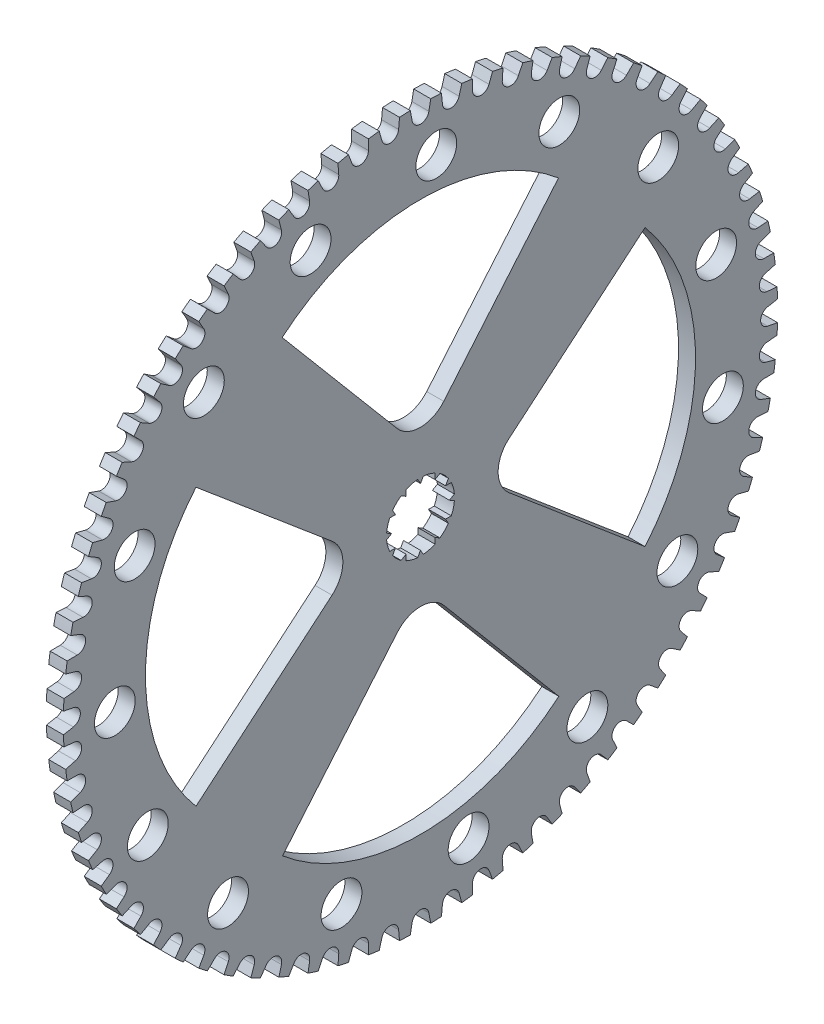
SolidWorks part; units mm, degrees
material "Chrome Stainless Steel"
ref_plane "Front Plane" through (0, 0, 0) normal (0, 0, 1) x (1, 0, 0)
ref_plane "Top Plane" through (0, 0, 0) normal (0, 1, 0) x (1, 0, 0)
ref_plane "Right Plane" through (0, 0, 0) normal (1, 0, 0) x (0, 0, -1)
sketch "Sketch1" plane through (0, 0, 0) normal (1, 0, 0) x (0, 0, -1)
  circle A0 centre (0, 0) radius 105
  dimension "D1" = 210
extrude "Boss-Extrude1" add sketch "Sketch1" along normal blind 5
sketch "Sketch3" plane through (0, 0, 0) normal (-1, 0, 0) x (0, 0, 1)
  line L0 (-2.4578, 102.0428) -> (-3, 104.9571)
  line L1 (2.4578, 102.0428) -> (3, 104.9571)
  line L2 (6.4451, 101.8687) -> (6.159, 104.8192)
  line L3 (11.3421, 101.4402) -> (12.1362, 104.2963)
  line L4 (15.299, 100.9193) -> (15.2712, 103.8835)
  line L5 (20.14, 100.0657) -> (21.18, 102.8417)
  line L6 (24.0365, 99.2019) -> (24.2671, 102.1573)
  line L7 (28.7847, 97.9296) -> (30.0627, 100.6043)
  line L8 (32.5911, 96.7295) -> (33.0784, 99.6535)
  line L9 (37.2103, 95.0482) -> (38.7165, 97.6014)
  line L10 (40.8976, 93.5209) -> (41.6379, 96.3913)
  line L11 (45.3527, 91.4434) -> (47.0757, 93.8556)
  line L12 (48.8928, 89.6005) -> (49.8805, 92.3955)
  line L13 (53.1499, 87.1427) -> (55.0766, 89.3955)
  line L14 (56.516, 84.9983) -> (57.7435, 87.6966)
  line L15 (60.5427, 82.1788) -> (62.6584, 84.2551)
  line L16 (63.709, 79.7492) -> (65.167, 82.3302)
  line L17 (67.4746, 76.5894) -> (69.7633, 78.4735)
  line L18 (70.4172, 73.8931) -> (72.0946, 76.3372)
  line L19 (73.8931, 70.4172) -> (76.3372, 72.0946)
  line L20 (76.5894, 67.4746) -> (78.4735, 69.7633)
  line L21 (79.7492, 63.709) -> (82.3302, 65.167)
  line L22 (82.1788, 60.5427) -> (84.2551, 62.6584)
  line L23 (84.9983, 56.516) -> (87.6966, 57.7435)
  line L24 (87.1427, 53.1499) -> (89.3955, 55.0766)
  line L25 (89.6005, 48.8928) -> (92.3955, 49.8805)
  line L26 (91.4434, 45.3527) -> (93.8556, 47.0757)
  line L27 (93.5209, 40.8976) -> (96.3913, 41.6379)
  line L28 (95.0482, 37.2103) -> (97.6014, 38.7165)
  line L29 (96.7295, 32.5911) -> (99.6535, 33.0784)
  line L30 (97.9296, 28.7847) -> (100.6043, 30.0627)
  line L31 (99.2019, 24.0365) -> (102.1573, 24.2671)
  line L32 (100.0657, 20.14) -> (102.8417, 21.18)
  line L33 (100.9193, 15.299) -> (103.8835, 15.2712)
  line L34 (101.4402, 11.3421) -> (104.2963, 12.1362)
  line L35 (101.8687, 6.4451) -> (104.8192, 6.159)
  line L36 (102.0428, 2.4578) -> (104.9571, 3)
  line L37 (102.0428, -2.4578) -> (104.9571, -3)
  line L38 (101.8687, -6.4451) -> (104.8192, -6.159)
  line L39 (101.4402, -11.3421) -> (104.2963, -12.1362)
  line L40 (100.9193, -15.299) -> (103.8835, -15.2712)
  line L41 (100.0657, -20.14) -> (102.8417, -21.18)
  line L42 (99.2019, -24.0365) -> (102.1573, -24.2671)
  line L43 (97.9296, -28.7847) -> (100.6043, -30.0627)
  line L44 (96.7295, -32.5911) -> (99.6535, -33.0784)
  line L45 (95.0482, -37.2103) -> (97.6014, -38.7165)
  line L46 (93.5209, -40.8976) -> (96.3913, -41.6379)
  line L47 (91.4434, -45.3527) -> (93.8556, -47.0757)
  line L48 (89.6005, -48.8928) -> (92.3955, -49.8805)
  line L49 (87.1427, -53.1499) -> (89.3955, -55.0766)
  line L50 (84.9983, -56.516) -> (87.6966, -57.7435)
  line L51 (82.1788, -60.5427) -> (84.2551, -62.6584)
  line L52 (79.7492, -63.709) -> (82.3302, -65.167)
  line L53 (76.5894, -67.4746) -> (78.4735, -69.7633)
  line L54 (73.8931, -70.4172) -> (76.3372, -72.0946)
  line L55 (70.4172, -73.8931) -> (72.0946, -76.3372)
  line L56 (67.4746, -76.5894) -> (69.7633, -78.4735)
  line L57 (63.709, -79.7492) -> (65.167, -82.3302)
  line L58 (60.5427, -82.1788) -> (62.6584, -84.2551)
  line L59 (56.516, -84.9983) -> (57.7435, -87.6966)
  line L60 (53.1499, -87.1427) -> (55.0766, -89.3955)
  line L61 (48.8928, -89.6005) -> (49.8805, -92.3955)
  line L62 (45.3527, -91.4434) -> (47.0757, -93.8556)
  line L63 (40.8976, -93.5209) -> (41.6379, -96.3913)
  line L64 (37.2103, -95.0482) -> (38.7165, -97.6014)
  line L65 (32.5911, -96.7295) -> (33.0784, -99.6535)
  line L66 (28.7847, -97.9296) -> (30.0627, -100.6043)
  line L67 (24.0365, -99.2019) -> (24.2671, -102.1573)
  line L68 (20.14, -100.0657) -> (21.18, -102.8417)
  line L69 (15.299, -100.9193) -> (15.2712, -103.8835)
  line L70 (11.3421, -101.4402) -> (12.1362, -104.2963)
  line L71 (6.4451, -101.8687) -> (6.159, -104.8192)
  line L72 (2.4578, -102.0428) -> (3, -104.9571)
  line L73 (-2.4578, -102.0428) -> (-3, -104.9571)
  line L74 (-6.4451, -101.8687) -> (-6.159, -104.8192)
  line L75 (-11.3421, -101.4402) -> (-12.1362, -104.2963)
  line L76 (-15.299, -100.9193) -> (-15.2712, -103.8835)
  line L77 (-20.14, -100.0657) -> (-21.18, -102.8417)
  line L78 (-24.0365, -99.2019) -> (-24.2671, -102.1573)
  line L79 (-28.7847, -97.9296) -> (-30.0627, -100.6043)
  line L80 (-32.5911, -96.7295) -> (-33.0784, -99.6535)
  line L81 (-37.2103, -95.0482) -> (-38.7165, -97.6014)
  line L82 (-40.8976, -93.5209) -> (-41.6379, -96.3913)
  line L83 (-45.3527, -91.4434) -> (-47.0757, -93.8556)
  line L84 (-48.8928, -89.6005) -> (-49.8805, -92.3955)
  line L85 (-53.1499, -87.1427) -> (-55.0766, -89.3955)
  line L86 (-56.516, -84.9983) -> (-57.7435, -87.6966)
  line L87 (-60.5427, -82.1788) -> (-62.6584, -84.2551)
  line L88 (-63.709, -79.7492) -> (-65.167, -82.3302)
  line L89 (-67.4746, -76.5894) -> (-69.7633, -78.4735)
  line L90 (-70.4172, -73.8931) -> (-72.0946, -76.3372)
  line L91 (-73.8931, -70.4172) -> (-76.3372, -72.0946)
  line L92 (-76.5894, -67.4746) -> (-78.4735, -69.7633)
  line L93 (-79.7492, -63.709) -> (-82.3302, -65.167)
  line L94 (-82.1788, -60.5427) -> (-84.2551, -62.6584)
  line L95 (-84.9983, -56.516) -> (-87.6966, -57.7435)
  line L96 (-87.1427, -53.1499) -> (-89.3955, -55.0766)
  line L97 (-89.6005, -48.8928) -> (-92.3955, -49.8805)
  line L98 (-91.4434, -45.3527) -> (-93.8556, -47.0757)
  line L99 (-93.5209, -40.8976) -> (-96.3913, -41.6379)
  line L100 (-95.0482, -37.2103) -> (-97.6014, -38.7165)
  line L101 (-96.7295, -32.5911) -> (-99.6535, -33.0784)
  line L102 (-97.9296, -28.7847) -> (-100.6043, -30.0627)
  line L103 (-99.2019, -24.0365) -> (-102.1573, -24.2671)
  line L104 (-100.0657, -20.14) -> (-102.8417, -21.18)
  line L105 (-100.9193, -15.299) -> (-103.8835, -15.2712)
  line L106 (-101.4402, -11.3421) -> (-104.2963, -12.1362)
  line L107 (-101.8687, -6.4451) -> (-104.8192, -6.159)
  line L108 (-102.0428, -2.4578) -> (-104.9571, -3)
  line L109 (-102.0428, 2.4578) -> (-104.9571, 3)
  line L110 (-101.8687, 6.4451) -> (-104.8192, 6.159)
  line L111 (-101.4402, 11.3421) -> (-104.2963, 12.1362)
  line L112 (-100.9193, 15.299) -> (-103.8835, 15.2712)
  line L113 (-100.0657, 20.14) -> (-102.8417, 21.18)
  line L114 (-99.2019, 24.0365) -> (-102.1573, 24.2671)
  line L115 (-97.9296, 28.7847) -> (-100.6043, 30.0627)
  line L116 (-96.7295, 32.5911) -> (-99.6535, 33.0784)
  line L117 (-95.0482, 37.2103) -> (-97.6014, 38.7165)
  line L118 (-93.5209, 40.8976) -> (-96.3913, 41.6379)
  line L119 (-91.4434, 45.3527) -> (-93.8556, 47.0757)
  line L120 (-89.6005, 48.8928) -> (-92.3955, 49.8805)
  line L121 (-87.1427, 53.1499) -> (-89.3955, 55.0766)
  line L122 (-84.9983, 56.516) -> (-87.6966, 57.7435)
  line L123 (-82.1788, 60.5427) -> (-84.2551, 62.6584)
  line L124 (-79.7492, 63.709) -> (-82.3302, 65.167)
  line L125 (-76.5894, 67.4746) -> (-78.4735, 69.7633)
  line L126 (-73.8931, 70.4172) -> (-76.3372, 72.0946)
  line L127 (-70.4172, 73.8931) -> (-72.0946, 76.3372)
  line L128 (-67.4746, 76.5894) -> (-69.7633, 78.4735)
  line L129 (-63.709, 79.7492) -> (-65.167, 82.3302)
  line L130 (-60.5427, 82.1788) -> (-62.6584, 84.2551)
  line L131 (-56.516, 84.9983) -> (-57.7435, 87.6966)
  line L132 (-53.1499, 87.1427) -> (-55.0766, 89.3955)
  line L133 (-48.8928, 89.6005) -> (-49.8805, 92.3955)
  line L134 (-45.3527, 91.4434) -> (-47.0757, 93.8556)
  line L135 (-40.8976, 93.5209) -> (-41.6379, 96.3913)
  line L136 (-37.2103, 95.0482) -> (-38.7165, 97.6014)
  line L137 (-32.5911, 96.7295) -> (-33.0784, 99.6535)
  line L138 (-28.7847, 97.9296) -> (-30.0627, 100.6043)
  line L139 (-24.0365, 99.2019) -> (-24.2671, 102.1573)
  line L140 (-20.14, 100.0657) -> (-21.18, 102.8417)
  line L141 (-15.299, 100.9193) -> (-15.2712, 103.8835)
  line L142 (-11.3421, 101.4402) -> (-12.1362, 104.2963)
  line L143 (-6.4451, 101.8687) -> (-6.159, 104.8192)
  line L164 (-0.8454, 9.9642) -> (0, 8.5)
  line L167 (0, 8.5) -> (0.8454, 9.9642)
  line L170 (4.25, 9.0519) -> (4.25, 7.3612)
  line L171 (4.25, 7.3612) -> (5.7142, 8.2066)
  line L172 (8.2066, 5.7142) -> (7.3612, 4.25)
  line L173 (7.3612, 4.25) -> (9.0519, 4.25)
  line L174 (9.9642, 0.8454) -> (8.5, 0)
  line L175 (8.5, 0) -> (9.9642, -0.8454)
  line L176 (9.0519, -4.25) -> (7.3612, -4.25)
  line L177 (7.3612, -4.25) -> (8.2066, -5.7142)
  line L178 (5.7142, -8.2066) -> (4.25, -7.3612)
  line L179 (4.25, -7.3612) -> (4.25, -9.0519)
  line L180 (0.8454, -9.9642) -> (0, -8.5)
  line L181 (0, -8.5) -> (-0.8454, -9.9642)
  line L182 (-4.25, -9.0519) -> (-4.25, -7.3612)
  line L183 (-4.25, -7.3612) -> (-5.7142, -8.2066)
  line L184 (-8.2066, -5.7142) -> (-7.3612, -4.25)
  line L185 (-7.3612, -4.25) -> (-9.0519, -4.25)
  line L186 (-9.9642, -0.8454) -> (-8.5, 0)
  line L187 (-8.5, 0) -> (-9.9642, 0.8454)
  line L188 (-9.0519, 4.25) -> (-7.3612, 4.25)
  line L189 (-7.3612, 4.25) -> (-8.2066, 5.7142)
  line L190 (-5.7142, 8.2066) -> (-4.25, 7.3612)
  line L191 (-4.25, 7.3612) -> (-4.25, 9.0519)
  arc A0 (2.4578, 102.0428) -> (-2.4578, 102.0428) centre (0, 102.5) cw
  circle A1 centre (0, 0) radius 105 construction
  circle A2 centre (0, 0) radius 100 construction
  arc A3 (-3, 104.9571) -> (3, 104.9571) centre (0, 0) cw
  arc A4 (11.3421, 101.4402) -> (6.4451, 101.8687) centre (8.9335, 102.11) cw
  arc A5 (6.159, 104.8192) -> (12.1362, 104.2963) centre (0, 0) cw
  arc A6 (20.14, 100.0657) -> (15.299, 100.9193) centre (17.7989, 100.9428) cw
  arc A7 (15.2712, 103.8835) -> (21.18, 102.8417) centre (0, 0) cw
  arc A8 (28.7847, 97.9296) -> (24.0365, 99.2019) centre (26.529, 99.0074) cw
  arc A9 (24.2671, 102.1573) -> (30.0627, 100.6043) centre (0, 0) cw
  arc A10 (37.2103, 95.0482) -> (32.5911, 96.7295) centre (35.0571, 96.3185) cw
  arc A11 (33.0784, 99.6535) -> (38.7165, 97.6014) centre (0, 0) cw
  arc A12 (45.3527, 91.4434) -> (40.8976, 93.5209) centre (43.3184, 92.8965) cw
  arc A13 (41.6379, 96.3913) -> (47.0757, 93.8556) centre (0, 0) cw
  arc A14 (53.1499, 87.1427) -> (48.8928, 89.6005) centre (51.25, 88.7676) cw
  arc A15 (49.8805, 92.3955) -> (55.0766, 89.3955) centre (0, 0) cw
  arc A16 (60.5427, 82.1788) -> (56.516, 84.9983) centre (58.7916, 83.9631) cw
  arc A17 (57.7435, 87.6966) -> (62.6584, 84.2551) centre (0, 0) cw
  arc A18 (67.4746, 76.5894) -> (63.709, 79.7492) centre (65.8857, 78.5196) cw
  arc A19 (65.167, 82.3302) -> (69.7633, 78.4735) centre (0, 0) cw
  arc A20 (73.8931, 70.4172) -> (70.4172, 73.8931) centre (72.4784, 72.4784) cw
  arc A21 (72.0946, 76.3372) -> (76.3372, 72.0946) centre (0, 0) cw
  arc A22 (79.7492, 63.709) -> (76.5894, 67.4746) centre (78.5196, 65.8857) cw
  arc A23 (78.4735, 69.7633) -> (82.3302, 65.167) centre (0, 0) cw
  arc A24 (84.9983, 56.516) -> (82.1788, 60.5427) centre (83.9631, 58.7916) cw
  arc A25 (84.2551, 62.6584) -> (87.6966, 57.7435) centre (0, 0) cw
  arc A26 (89.6005, 48.8928) -> (87.1427, 53.1499) centre (88.7676, 51.25) cw
  arc A27 (89.3955, 55.0766) -> (92.3955, 49.8805) centre (0, 0) cw
  arc A28 (93.5209, 40.8976) -> (91.4434, 45.3527) centre (92.8965, 43.3184) cw
  arc A29 (93.8556, 47.0757) -> (96.3913, 41.6379) centre (0, 0) cw
  arc A30 (96.7295, 32.5911) -> (95.0482, 37.2103) centre (96.3185, 35.0571) cw
  arc A31 (97.6014, 38.7165) -> (99.6535, 33.0784) centre (0, 0) cw
  arc A32 (99.2019, 24.0365) -> (97.9296, 28.7847) centre (99.0074, 26.529) cw
  arc A33 (100.6043, 30.0627) -> (102.1573, 24.2671) centre (0, 0) cw
  arc A34 (100.9193, 15.299) -> (100.0657, 20.14) centre (100.9428, 17.7989) cw
  arc A35 (102.8417, 21.18) -> (103.8835, 15.2712) centre (0, 0) cw
  arc A36 (101.8687, 6.4451) -> (101.4402, 11.3421) centre (102.11, 8.9335) cw
  arc A37 (104.2963, 12.1362) -> (104.8192, 6.159) centre (0, 0) cw
  arc A38 (102.0428, -2.4578) -> (102.0428, 2.4578) centre (102.5, 0) cw
  arc A39 (104.9571, 3) -> (104.9571, -3) centre (0, 0) cw
  arc A40 (101.4402, -11.3421) -> (101.8687, -6.4451) centre (102.11, -8.9335) cw
  arc A41 (104.8192, -6.159) -> (104.2963, -12.1362) centre (0, 0) cw
  arc A42 (100.0657, -20.14) -> (100.9193, -15.299) centre (100.9428, -17.7989) cw
  arc A43 (103.8835, -15.2712) -> (102.8417, -21.18) centre (0, 0) cw
  arc A44 (97.9296, -28.7847) -> (99.2019, -24.0365) centre (99.0074, -26.529) cw
  arc A45 (102.1573, -24.2671) -> (100.6043, -30.0627) centre (0, 0) cw
  arc A46 (95.0482, -37.2103) -> (96.7295, -32.5911) centre (96.3185, -35.0571) cw
  arc A47 (99.6535, -33.0784) -> (97.6014, -38.7165) centre (0, 0) cw
  arc A48 (91.4434, -45.3527) -> (93.5209, -40.8976) centre (92.8965, -43.3184) cw
  arc A49 (96.3913, -41.6379) -> (93.8556, -47.0757) centre (0, 0) cw
  arc A50 (87.1427, -53.1499) -> (89.6005, -48.8928) centre (88.7676, -51.25) cw
  arc A51 (92.3955, -49.8805) -> (89.3955, -55.0766) centre (0, 0) cw
  arc A52 (82.1788, -60.5427) -> (84.9983, -56.516) centre (83.9631, -58.7916) cw
  arc A53 (87.6966, -57.7435) -> (84.2551, -62.6584) centre (0, 0) cw
  arc A54 (76.5894, -67.4746) -> (79.7492, -63.709) centre (78.5196, -65.8857) cw
  arc A55 (82.3302, -65.167) -> (78.4735, -69.7633) centre (0, 0) cw
  arc A56 (70.4172, -73.8931) -> (73.8931, -70.4172) centre (72.4784, -72.4784) cw
  arc A57 (76.3372, -72.0946) -> (72.0946, -76.3372) centre (0, 0) cw
  arc A58 (63.709, -79.7492) -> (67.4746, -76.5894) centre (65.8857, -78.5196) cw
  arc A59 (69.7633, -78.4735) -> (65.167, -82.3302) centre (0, 0) cw
  arc A60 (56.516, -84.9983) -> (60.5427, -82.1788) centre (58.7916, -83.9631) cw
  arc A61 (62.6584, -84.2551) -> (57.7435, -87.6966) centre (0, 0) cw
  arc A62 (48.8928, -89.6005) -> (53.1499, -87.1427) centre (51.25, -88.7676) cw
  arc A63 (55.0766, -89.3955) -> (49.8805, -92.3955) centre (0, 0) cw
  arc A64 (40.8976, -93.5209) -> (45.3527, -91.4434) centre (43.3184, -92.8965) cw
  arc A65 (47.0757, -93.8556) -> (41.6379, -96.3913) centre (0, 0) cw
  arc A66 (32.5911, -96.7295) -> (37.2103, -95.0482) centre (35.0571, -96.3185) cw
  arc A67 (38.7165, -97.6014) -> (33.0784, -99.6535) centre (0, 0) cw
  arc A68 (24.0365, -99.2019) -> (28.7847, -97.9296) centre (26.529, -99.0074) cw
  arc A69 (30.0627, -100.6043) -> (24.2671, -102.1573) centre (0, 0) cw
  arc A70 (15.299, -100.9193) -> (20.14, -100.0657) centre (17.7989, -100.9428) cw
  arc A71 (21.18, -102.8417) -> (15.2712, -103.8835) centre (0, 0) cw
  arc A72 (6.4451, -101.8687) -> (11.3421, -101.4402) centre (8.9335, -102.11) cw
  arc A73 (12.1362, -104.2963) -> (6.159, -104.8192) centre (0, 0) cw
  arc A74 (-2.4578, -102.0428) -> (2.4578, -102.0428) centre (0, -102.5) cw
  arc A75 (3, -104.9571) -> (-3, -104.9571) centre (0, 0) cw
  arc A76 (-11.3421, -101.4402) -> (-6.4451, -101.8687) centre (-8.9335, -102.11) cw
  arc A77 (-6.159, -104.8192) -> (-12.1362, -104.2963) centre (0, 0) cw
  arc A78 (-20.14, -100.0657) -> (-15.299, -100.9193) centre (-17.7989, -100.9428) cw
  arc A79 (-15.2712, -103.8835) -> (-21.18, -102.8417) centre (0, 0) cw
  arc A80 (-28.7847, -97.9296) -> (-24.0365, -99.2019) centre (-26.529, -99.0074) cw
  arc A81 (-24.2671, -102.1573) -> (-30.0627, -100.6043) centre (0, 0) cw
  arc A82 (-37.2103, -95.0482) -> (-32.5911, -96.7295) centre (-35.0571, -96.3185) cw
  arc A83 (-33.0784, -99.6535) -> (-38.7165, -97.6014) centre (0, 0) cw
  arc A84 (-45.3527, -91.4434) -> (-40.8976, -93.5209) centre (-43.3184, -92.8965) cw
  arc A85 (-41.6379, -96.3913) -> (-47.0757, -93.8556) centre (0, 0) cw
  arc A86 (-53.1499, -87.1427) -> (-48.8928, -89.6005) centre (-51.25, -88.7676) cw
  arc A87 (-49.8805, -92.3955) -> (-55.0766, -89.3955) centre (0, 0) cw
  arc A88 (-60.5427, -82.1788) -> (-56.516, -84.9983) centre (-58.7916, -83.9631) cw
  arc A89 (-57.7435, -87.6966) -> (-62.6584, -84.2551) centre (0, 0) cw
  arc A90 (-67.4746, -76.5894) -> (-63.709, -79.7492) centre (-65.8857, -78.5196) cw
  arc A91 (-65.167, -82.3302) -> (-69.7633, -78.4735) centre (0, 0) cw
  arc A92 (-73.8931, -70.4172) -> (-70.4172, -73.8931) centre (-72.4784, -72.4784) cw
  arc A93 (-72.0946, -76.3372) -> (-76.3372, -72.0946) centre (0, 0) cw
  arc A94 (-79.7492, -63.709) -> (-76.5894, -67.4746) centre (-78.5196, -65.8857) cw
  arc A95 (-78.4735, -69.7633) -> (-82.3302, -65.167) centre (0, 0) cw
  arc A96 (-84.9983, -56.516) -> (-82.1788, -60.5427) centre (-83.9631, -58.7916) cw
  arc A97 (-84.2551, -62.6584) -> (-87.6966, -57.7435) centre (0, 0) cw
  arc A98 (-89.6005, -48.8928) -> (-87.1427, -53.1499) centre (-88.7676, -51.25) cw
  arc A99 (-89.3955, -55.0766) -> (-92.3955, -49.8805) centre (0, 0) cw
  arc A100 (-93.5209, -40.8976) -> (-91.4434, -45.3527) centre (-92.8965, -43.3184) cw
  arc A101 (-93.8556, -47.0757) -> (-96.3913, -41.6379) centre (0, 0) cw
  arc A102 (-96.7295, -32.5911) -> (-95.0482, -37.2103) centre (-96.3185, -35.0571) cw
  arc A103 (-97.6014, -38.7165) -> (-99.6535, -33.0784) centre (0, 0) cw
  arc A104 (-99.2019, -24.0365) -> (-97.9296, -28.7847) centre (-99.0074, -26.529) cw
  arc A105 (-100.6043, -30.0627) -> (-102.1573, -24.2671) centre (0, 0) cw
  arc A106 (-100.9193, -15.299) -> (-100.0657, -20.14) centre (-100.9428, -17.7989) cw
  arc A107 (-102.8417, -21.18) -> (-103.8835, -15.2712) centre (0, 0) cw
  arc A108 (-101.8687, -6.4451) -> (-101.4402, -11.3421) centre (-102.11, -8.9335) cw
  arc A109 (-104.2963, -12.1362) -> (-104.8192, -6.159) centre (0, 0) cw
  arc A110 (-102.0428, 2.4578) -> (-102.0428, -2.4578) centre (-102.5, 0) cw
  arc A111 (-104.9571, -3) -> (-104.9571, 3) centre (0, 0) cw
  arc A112 (-101.4402, 11.3421) -> (-101.8687, 6.4451) centre (-102.11, 8.9335) cw
  arc A113 (-104.8192, 6.159) -> (-104.2963, 12.1362) centre (0, 0) cw
  arc A114 (-100.0657, 20.14) -> (-100.9193, 15.299) centre (-100.9428, 17.7989) cw
  arc A115 (-103.8835, 15.2712) -> (-102.8417, 21.18) centre (0, 0) cw
  arc A116 (-97.9296, 28.7847) -> (-99.2019, 24.0365) centre (-99.0074, 26.529) cw
  arc A117 (-102.1573, 24.2671) -> (-100.6043, 30.0627) centre (0, 0) cw
  arc A118 (-95.0482, 37.2103) -> (-96.7295, 32.5911) centre (-96.3185, 35.0571) cw
  arc A119 (-99.6535, 33.0784) -> (-97.6014, 38.7165) centre (0, 0) cw
  arc A120 (-91.4434, 45.3527) -> (-93.5209, 40.8976) centre (-92.8965, 43.3184) cw
  arc A121 (-96.3913, 41.6379) -> (-93.8556, 47.0757) centre (0, 0) cw
  arc A122 (-87.1427, 53.1499) -> (-89.6005, 48.8928) centre (-88.7676, 51.25) cw
  arc A123 (-92.3955, 49.8805) -> (-89.3955, 55.0766) centre (0, 0) cw
  arc A124 (-82.1788, 60.5427) -> (-84.9983, 56.516) centre (-83.9631, 58.7916) cw
  arc A125 (-87.6966, 57.7435) -> (-84.2551, 62.6584) centre (0, 0) cw
  arc A126 (-76.5894, 67.4746) -> (-79.7492, 63.709) centre (-78.5196, 65.8857) cw
  arc A127 (-82.3302, 65.167) -> (-78.4735, 69.7633) centre (0, 0) cw
  arc A128 (-70.4172, 73.8931) -> (-73.8931, 70.4172) centre (-72.4784, 72.4784) cw
  arc A129 (-76.3372, 72.0946) -> (-72.0946, 76.3372) centre (0, 0) cw
  arc A130 (-63.709, 79.7492) -> (-67.4746, 76.5894) centre (-65.8857, 78.5196) cw
  arc A131 (-69.7633, 78.4735) -> (-65.167, 82.3302) centre (0, 0) cw
  arc A132 (-56.516, 84.9983) -> (-60.5427, 82.1788) centre (-58.7916, 83.9631) cw
  arc A133 (-62.6584, 84.2551) -> (-57.7435, 87.6966) centre (0, 0) cw
  arc A134 (-48.8928, 89.6005) -> (-53.1499, 87.1427) centre (-51.25, 88.7676) cw
  arc A135 (-55.0766, 89.3955) -> (-49.8805, 92.3955) centre (0, 0) cw
  arc A136 (-40.8976, 93.5209) -> (-45.3527, 91.4434) centre (-43.3184, 92.8965) cw
  arc A137 (-47.0757, 93.8556) -> (-41.6379, 96.3913) centre (0, 0) cw
  arc A138 (-32.5911, 96.7295) -> (-37.2103, 95.0482) centre (-35.0571, 96.3185) cw
  arc A139 (-38.7165, 97.6014) -> (-33.0784, 99.6535) centre (0, 0) cw
  arc A140 (-24.0365, 99.2019) -> (-28.7847, 97.9296) centre (-26.529, 99.0074) cw
  arc A141 (-30.0627, 100.6043) -> (-24.2671, 102.1573) centre (0, 0) cw
  arc A142 (-15.299, 100.9193) -> (-20.14, 100.0657) centre (-17.7989, 100.9428) cw
  arc A143 (-21.18, 102.8417) -> (-15.2712, 103.8835) centre (0, 0) cw
  arc A144 (-6.4451, 101.8687) -> (-11.3421, 101.4402) centre (-8.9335, 102.11) cw
  arc A145 (-12.1362, 104.2963) -> (-6.159, 104.8192) centre (0, 0) cw
  arc A165 (-5.7142, 8.2066) -> (-8.2066, 5.7142) centre (0, 0) ccw
  arc A166 (-0.8454, 9.9642) -> (-4.25, 9.0519) centre (0, 0) ccw
  arc A167 (4.25, 9.0519) -> (0.8454, 9.9642) centre (0, 0) ccw
  arc A168 (8.2066, 5.7142) -> (5.7142, 8.2066) centre (0, 0) ccw
  arc A169 (9.9642, 0.8454) -> (9.0519, 4.25) centre (0, 0) ccw
  arc A170 (9.0519, -4.25) -> (9.9642, -0.8454) centre (0, 0) ccw
  arc A171 (5.7142, -8.2066) -> (8.2066, -5.7142) centre (0, 0) ccw
  arc A172 (0.8454, -9.9642) -> (4.25, -9.0519) centre (0, 0) ccw
  arc A173 (-4.25, -9.0519) -> (-0.8454, -9.9642) centre (0, 0) ccw
  arc A174 (-8.2066, -5.7142) -> (-5.7142, -8.2066) centre (0, 0) ccw
  arc A175 (-9.9642, -0.8454) -> (-9.0519, -4.25) centre (0, 0) ccw
  arc A176 (-9.0519, 4.25) -> (-9.9642, 0.8454) centre (0, 0) ccw
  point P405 (0, 0)
  dimension "D1" = 2.5
  dimension "D2" = 200
  dimension "D4" = 72
  dimension "D5" = 20
  dimension "D8" = 12
  dimension "D6" = 60
  dimension "D3" = 6
  dimension "D7" = 8.5
extrude "Cut-Extrude4" cut sketch "Sketch3" against normal blind 10
extrude "Cut-Extrude2" cut sketch "Sketch4" against normal blind 36 and the other way blind 134
sketch "Sketch4" plane through (0, 0, 0) normal (1, 0, 0) x (0, 0, -1)
  line L2 (66.0126, -40.5708) -> (26.0126, -6.8291)
  line L4 (-6.9296, 26.0126) -> (-40.6713, 66.0126)
  line L5 (40.5708, 66.0126) -> (6.8291, 26.0126)
  line L6 (26.0126, 6.9296) -> (66.0126, 40.6713)
  line L7 (-40.5708, -66.0126) -> (-6.8291, -26.0126)
  line L8 (6.9296, -26.0126) -> (40.6713, -66.0126)
  line L9 (-66.0126, 40.5708) -> (-26.0126, 6.8291)
  line L10 (-26.0126, -6.9296) -> (-66.0126, -40.6713)
  arc A1 (-40.6713, 66.0126) -> (40.5708, 66.0126) centre (-0.0503, 17.8573) cw
  arc A3 (-6.9296, 26.0126) -> (6.8291, 26.0126) centre (-0.0503, 31.8156) ccw
  arc A4 (26.0126, 6.9296) -> (26.0126, -6.8291) centre (31.8156, 0.0503) ccw
  arc A5 (66.0126, 40.6713) -> (66.0126, -40.5708) centre (17.8573, 0.0503) cw
  arc A6 (6.9296, -26.0126) -> (-6.8291, -26.0126) centre (0.0503, -31.8156) ccw
  arc A7 (40.6713, -66.0126) -> (-40.5708, -66.0126) centre (0.0503, -17.8573) cw
  arc A8 (-26.0126, -6.9296) -> (-26.0126, 6.8291) centre (-31.8156, -0.0503) ccw
  arc A9 (-66.0126, -40.6713) -> (-66.0126, 40.5708) centre (-17.8573, -0.0503) cw
  point P10 (0, 17.7392)
  point P28 (0, 0)
extrude "Cut-Extrude3" cut sketch "Sketch5" against normal blind 16 and the other way blind 43
sketch "Sketch5" plane through (0, 0, 0) normal (1, 0, 0) x (0, 0, -1)
  line L0 (-66.0126, 40.5708) -> (-63.6852, 63.594) construction
  line L1 (-63.6852, 63.594) -> (-40.6713, 66.0126) construction
  circle A0 centre (-84.0453, 32.1929) radius 6
  circle A2 centre (-63.6852, 63.594) radius 6
  circle A3 centre (-32.3133, 83.9991) radius 6
  circle A4 centre (4.6459, 89.88) radius 6
  circle A5 centre (40.8017, 80.2198) radius 6
  circle A6 centre (69.9026, 56.6889) radius 6
  circle A7 centre (86.9166, 23.356) radius 6
  circle A8 centre (88.902, -14.0155) radius 6
  circle A9 centre (75.5154, -48.9635) radius 6
  circle A10 centre (49.0715, -75.4452) radius 6
  circle A11 centre (14.1427, -88.8818) radius 6
  circle A12 centre (-23.2315, -86.95) radius 6
  circle A13 centre (-56.5887, -69.9837) radius 6
  circle A14 centre (-80.1613, -40.9166) radius 6
  circle A15 centre (-89.8733, -4.7746) radius 6
  point P36 (0, 0)
